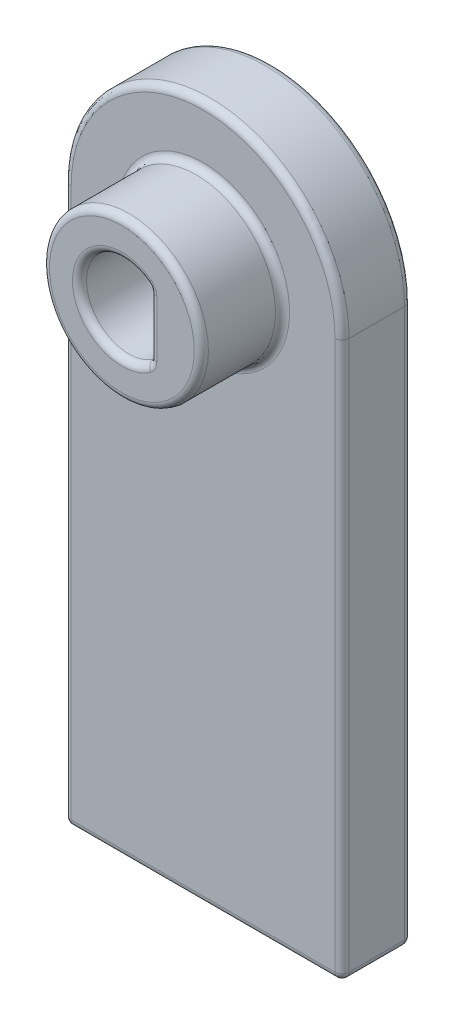
SolidWorks part; units mm, degrees
ref_plane "Front Plane" through (0, 0, 0) normal (0, 0, 1) x (1, 0, 0)
ref_plane "Top Plane" through (0, 0, 0) normal (0, 1, 0) x (1, 0, 0)
ref_plane "Right Plane" through (0, 0, 0) normal (1, 0, 0) x (0, 0, -1)
sketch "Sketch1" plane through (0, 0, 0) normal (0, 0, 1) x (1, 0, 0)
  line L0 (-10, 0) -> (-10, -40)
  line L1 (-10, -40) -> (10, -40)
  line L2 (10, -40) -> (10, 0)
  arc A0 (-10, 0) -> (10, 0) centre (0, 0) cw
  dimension "D1" = 10
  dimension "D2" = 40
extrude "Boss-Extrude1" add sketch "Sketch1" along normal blind 5
sketch "Sketch2" plane through (0, 0, 5) normal (0, 0, 1) x (1, 0, 0)
  line L3 (2.0031, 2.3) -> (2.0031, -2.3)
  circle A0 centre (0, 0) radius 5.715
  arc A10 (2.0031, 2.3) -> (2.0031, -2.3) centre (0, 0) ccw
  point P5 (0, -0.0971)
  dimension "D1" = 11.43
  dimension "D3" = 4.6
  dimension "D2" = 6.1
extrude "Boss-Extrude2" add sketch "Sketch2" along normal blind 5.842
sketch "Sketch3" plane through (0, 0, 5) normal (0, 0, 1) x (1, 0, 0)
  line L3 (2.0031, 2.3) -> (2.0031, -2.3)
  arc A12 (2.0031, 2.3) -> (2.0031, -2.3) centre (0, 0) ccw
  arc A13 (2.0031, 2.3) -> (2.0031, -2.3) centre (0, 0) ccw construction
extrude "Cut-Extrude1" cut sketch "Sketch3" against normal up to next
fillet "Fillet1" radius 0.508 18 edges at (5.715, 0, 10.842) (-5.715, 0, 5) (10, -20, 5) (-10, -20, 5) (10, -20, 0) (-10, -20, 0) (-10, -40, 2.5) (0, -40, 5) (10, -40, 2.5) (0, -40, 0) (0, 10, 5) (0, 10, 0) (2.0031, 0, 10.842) (2.0031, 0, 0) (-3.05, 0, 10.842) (2.0031, 2.3, 5.421) (2.0031, -2.3, 5.421) (-3.05, 0, 0)
